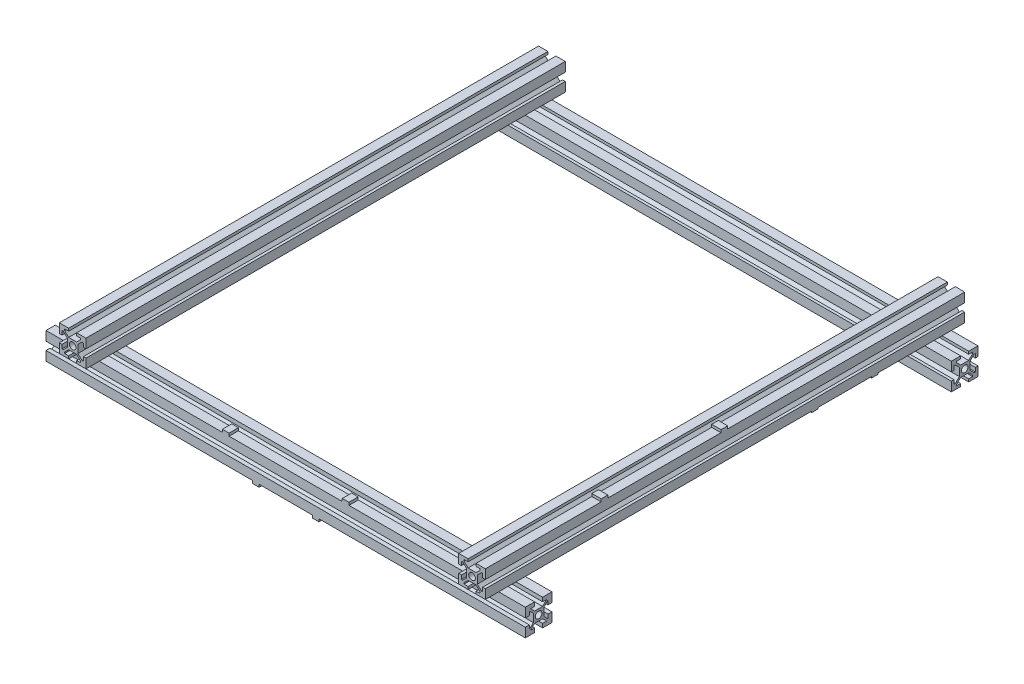
SolidWorks part; units mm, degrees
ref_plane "Front Plane" through (0, 0, 0) normal (0, 0, 1) x (1, 0, 0)
ref_plane "Top Plane" through (0, 0, 0) normal (0, 1, 0) x (1, 0, 0)
ref_plane "Right Plane" through (0, 0, 0) normal (1, 0, 0) x (0, 0, -1)
sketch "Sketch1" plane through (0, 0, 0) normal (0, 1, 0) x (1, 0, 0)
  line L1 (-180, 180) -> (180, 180)
  line L2 (-180, 180) -> (-180, -180)
  line L3 (-180, -180) -> (180, -180)
  line L4 (180, 180) -> (180, -180)
  line L5 (-180, 180) -> (180, -180) construction
  line L6 (-180, -180) -> (180, 180) construction
  point P0 (0, 0)
  dimension "D1" = 360
  dimension "D2" = 360
extrude "Boss-Extrude1" add sketch "Sketch1" along normal blind 20
sketch "Sketch2" plane through (0, 20, 0) normal (0, 1, 0) x (1, 0, 0)
  line L0 (-180, 180) -> (-180, -180) construction
  line L1 (-160, 160) -> (160, 160)
  line L2 (-160, 160) -> (-160, -160)
  line L3 (-160, -160) -> (160, -160)
  line L4 (160, 160) -> (160, -160)
  line L5 (-160, 160) -> (160, -160) construction
  line L6 (-160, -160) -> (160, 160) construction
  line L7 (-160, 160) -> (-140, 160)
  line L8 (-160, 160) -> (-160, -160)
  line L9 (-160, -160) -> (-140, -160)
  line L10 (-140, 160) -> (-140, -160)
  line L11 (160, 160) -> (140, 160)
  line L12 (160, 160) -> (160, -160)
  line L13 (160, -160) -> (140, -160)
  line L14 (140, 160) -> (140, -160)
  line L15 (-160, 160) -> (-180, 160)
  line L16 (-160, 160) -> (-160, -160)
  line L17 (-160, -160) -> (-180, -160)
  line L18 (-180, 160) -> (-180, -160)
  line L19 (180, -180) -> (180, 180) construction
  line L20 (160, 160) -> (180, 160)
  line L21 (160, 160) -> (160, -160)
  line L22 (160, -160) -> (180, -160)
  line L23 (180, 160) -> (180, -160)
  line L24 (180, 180) -> (-180, 180) construction
  line L25 (-140, 160) -> (140, 160)
  line L26 (-140, 160) -> (-140, 180)
  line L27 (-140, 180) -> (140, 180)
  line L28 (140, 160) -> (140, 180)
  line L29 (-180, -180) -> (180, -180) construction
  line L31 (-140, -180) -> (140, -180)
  line L32 (-140, -180) -> (-140, -160)
  line L33 (-140, -160) -> (140, -160)
  line L34 (140, -180) -> (140, -160)
  line L35 (160, -160) -> (180, -160)
  line L36 (160, -160) -> (160, -180)
  line L37 (160, -180) -> (180, -180)
  line L38 (180, -160) -> (180, -180)
  line L39 (-160, -160) -> (-180, -160)
  line L40 (-160, -160) -> (-160, -180)
  line L41 (-160, -180) -> (-180, -180)
  line L42 (-180, -160) -> (-180, -180)
  line L43 (-160, 160) -> (-180, 160)
  line L44 (-160, 160) -> (-160, 180)
  line L45 (-160, 180) -> (-180, 180)
  line L46 (-180, 160) -> (-180, 180)
  line L47 (160, 160) -> (180, 160)
  line L48 (160, 160) -> (160, 180)
  line L49 (160, 180) -> (180, 180)
  line L50 (180, 160) -> (180, 180)
  point P0 (0, 0)
  line M17 (180, -180) -> (180, 180)
  line M19 (-180, 180) -> (-180, -180)
  dimension "D1" = 320
  dimension "D2" = 320
  dimension "D3" = 20
  dimension "D4" = 20
extrude "Cut-Extrude1" cut sketch "Sketch2" against normal through all contours L17 L2 L15 M19 | L4 L22 L20 M17 | L14 L1 L10 L3
sketch "Sketch3" plane through (0, 0, 0) normal (0, -1, 0) x (1, 0, 0)
  line L1 (-180, 180) -> (180, 180)
  line L2 (-180, 180) -> (-180, 160)
  line L3 (-180, 160) -> (180, 160)
  line L4 (180, 180) -> (180, 160)
  line L5 (-180, -160) -> (180, -160)
  line L6 (-180, -160) -> (-180, -180)
  line L7 (-180, -180) -> (180, -180)
  line L8 (180, -160) -> (180, -180)
extrude "Boss-Extrude2" add sketch "Sketch3" along normal blind 20
sketch "Sketch4" plane through (0, 20, 0) normal (0, 1, 0) x (1, 0, 0)
  line L0 (-180, -180) -> (180, -180) construction
  line L1 (160, -160) -> (180, -160)
  line L2 (160, -160) -> (160, -180)
  line L3 (160, -180) -> (180, -180)
  line L4 (180, -160) -> (180, -180)
  line L5 (-180, -160) -> (-160, -160)
  line L6 (-180, -160) -> (-180, -180)
  line L7 (-180, -180) -> (-160, -180)
  line L8 (-160, -160) -> (-160, -180)
  line L10 (-180, 180) -> (-160, 180)
  line L11 (-180, 180) -> (-180, 160)
  line L12 (-180, 160) -> (-160, 160)
  line L13 (-160, 180) -> (-160, 160)
  line L14 (160, 160) -> (180, 160)
  line L15 (160, 160) -> (160, 180)
  line L16 (160, 180) -> (180, 180)
  line L17 (180, 160) -> (180, 180)
extrude "Cut-Extrude2" cut sketch "Sketch4" against normal blind 20
sketch "Sketch5" plane through (0, 20, 0) normal (0, 1, 0) x (1, 0, 0)
  line L0 (160, 180) -> (-160, 180) construction
  line L1 (-140, 160) -> (140, 160)
  line L2 (-140, 160) -> (-140, 180)
  line L3 (-140, 180) -> (140, 180)
  line L4 (140, 160) -> (140, 180)
  line L5 (-160, -180) -> (160, -180) construction
  line L6 (-140, -180) -> (140, -180)
  line L7 (-140, -180) -> (-140, -160)
  line L8 (-140, -160) -> (140, -160)
  line L9 (140, -180) -> (140, -160)
extrude "Cut-Extrude3" cut sketch "Sketch5" against normal blind 20
sketch "Sketch6" plane through (0, 0, -160) normal (0, 0, 1) x (1, 0, 0)
  line L1 (-180, 0) -> (180, 0)
  line L2 (-180, 0) -> (-180, -20)
  line L3 (-180, -20) -> (180, -20)
  line L4 (180, 0) -> (180, -20)
extrude "Boss-Extrude3" add sketch "Sketch6" along normal blind 10
sketch "Sketch7" plane through (0, 0, 160) normal (0, 0, -1) x (-1, 0, 0)
  line L1 (-180, 0) -> (180, 0)
  line L2 (-180, 0) -> (-180, -20)
  line L3 (-180, -20) -> (180, -20)
  line L4 (180, 0) -> (180, -20)
extrude "Boss-Extrude4" add sketch "Sketch7" along normal blind 10
sketch "Sketch8" plane through (0, 0, -180) normal (0, 0, -1) x (-1, 0, 0)
  line L1 (-180, 0) -> (180, 0)
  line L2 (-180, 0) -> (-180, -20)
  line L3 (-180, -20) -> (180, -20)
  line L4 (180, 0) -> (180, -20)
extrude "Cut-Extrude4" cut sketch "Sketch8" against normal blind 10
sketch "Sketch9" plane through (0, 0, 180) normal (0, 0, 1) x (1, 0, 0)
  line L1 (180, 0) -> (-180, 0)
  line L2 (180, 0) -> (180, -20)
  line L3 (180, -20) -> (-180, -20)
  line L4 (-180, 0) -> (-180, -20)
extrude "Cut-Extrude5" cut sketch "Sketch9" against normal blind 10
sketch "Sketch10" plane through (0, 0, -180) normal (0, 0, -1) x (-1, 0, 0)
  line L0 (140, 20) -> (160, 0) construction
  circle A0 centre (150, 10) radius 2.5
  dimension "D1" = 5
extrude "Cut-Extrude6" cut sketch "Sketch10" against normal through all
sketch "Sketch11" plane through (0, 0, 180) normal (0, 0, 1) x (1, 0, 0)
  line L0 (-160, 20) -> (-140, 0)
  line L1 (-160, 0) -> (-140, 20)
  line L2 (-154, 14) -> (-146, 14)
  line L3 (-154, 14) -> (-154, 6)
  line L4 (-154, 6) -> (-146, 6)
  line L5 (-146, 14) -> (-146, 6)
  line L6 (-154, 14) -> (-146, 6) construction
  line L7 (-154, 6) -> (-146, 14) construction
  line L8 (-154, 14) -> (-153, 14)
  line L9 (-154, 14) -> (-154, 13)
  line L10 (-154, 13) -> (-153, 13)
  line L11 (-153, 14) -> (-153, 13)
  line L12 (-146, 14) -> (-147, 14)
  line L13 (-146, 14) -> (-146, 13)
  line L14 (-146, 13) -> (-147, 13)
  line L15 (-147, 14) -> (-147, 13)
  line L16 (-154, 6) -> (-153, 6)
  line L17 (-154, 6) -> (-154, 7)
  line L18 (-154, 7) -> (-153, 7)
  line L19 (-153, 6) -> (-153, 7)
  line L20 (-146, 6) -> (-147, 6)
  line L21 (-146, 6) -> (-146, 7)
  line L22 (-146, 7) -> (-147, 7)
  line L23 (-147, 6) -> (-147, 7)
  line L24 (-160, 20) -> (-156, 20)
  line L25 (-160, 20) -> (-160, 16)
  line L26 (-160, 16) -> (-156, 16)
  line L27 (-156, 20) -> (-156, 16)
  line L28 (-153, 14) -> (-156, 17)
  line L29 (-140, 20) -> (-144, 20)
  line L30 (-140, 20) -> (-140, 16)
  line L31 (-140, 16) -> (-144, 16)
  line L32 (-144, 20) -> (-144, 16)
  line L33 (-160, 0) -> (-156, 0)
  line L34 (-160, 0) -> (-160, 4)
  line L35 (-160, 4) -> (-156, 4)
  line L36 (-156, 0) -> (-156, 4)
  line L37 (-140, 0) -> (-144, 0)
  line L38 (-140, 0) -> (-140, 4)
  line L39 (-140, 4) -> (-144, 4)
  line L40 (-144, 0) -> (-144, 4)
  line L41 (-154, 13) -> (-157, 16)
  line L42 (-157, 16) -> (-157, 4) construction
  line L43 (-156, 17) -> (-144.0513, 17) construction
  line L44 (-144.0513, 17) -> (-144, 17) construction
  line L45 (-157, 4) -> (-154.0345, 7.0171)
  line L46 (-154.0345, 7.0171) -> (-153, 6)
  line L47 (-153, 6) -> (-156, 2.9486)
  line L48 (-156, 2.9486) -> (-144, 2.9486) construction
  line L49 (-144, 2.9486) -> (-142.9741, 3.9745) construction
  line L50 (-142.9741, 3.9745) -> (-142.9741, 16) construction
  line L51 (-142.9741, 16) -> (-146, 12.9741)
  line L52 (-147, 6) -> (-144, 2.9486)
  line L53 (-146, 7) -> (-142.9741, 3.9745)
  line L54 (-153, 14) -> (-147, 14)
  line L55 (-156, 20) -> (-144, 20)
  line L56 (-156, 20) -> (-156, 18)
  line L57 (-156, 18) -> (-144, 18)
  line L58 (-144, 20) -> (-144, 18)
  line L59 (-160, 16) -> (-158, 16)
  line L60 (-160, 16) -> (-160, 4)
  line L61 (-160, 4) -> (-158, 4)
  line L62 (-158, 16) -> (-158, 4)
  line L63 (-140, 16) -> (-142, 16)
  line L64 (-140, 16) -> (-140, 4)
  line L65 (-140, 4) -> (-142, 4)
  line L66 (-142, 16) -> (-142, 4)
  line L67 (-156, 0) -> (-144, 0)
  line L68 (-156, 0) -> (-156, 2)
  line L69 (-156, 2) -> (-144, 2)
  line L70 (-144, 0) -> (-144, 2)
  line L71 (-156, 17) -> (-156, 18.0394)
  line L72 (-156, 18.0394) -> (-144, 18)
  line L73 (-147, 14) -> (-144, 17)
  point P4 (-150, 10)
  dimension "D1" = 8
  dimension "D2" = 1
  dimension "D3" = 1
  dimension "D4" = 1
  dimension "D5" = 1
  dimension "D6" = 4
  dimension "D7" = 4
  dimension "D8" = 4
  dimension "D9" = 4
  dimension "D10" = 2
  dimension "D11" = 2
  dimension "D12" = 2
  dimension "D13" = 2
extrude "Cut-Extrude7" cut sketch "Sketch11" against normal through all contours L26 L62 L35 L45 L46 L3 L41 | L2 L73 L32 L57 L27 L28 | L66 L31 L51 L5 L53 L39 | L36 L69 L40 L52 L4 L47
sketch "Sketch12" plane through (0, 0, 180) normal (0, 0, 1) x (1, 0, 0)
  line L0 (-160, 20) -> (-140, 0) construction
  line L1 (-140, 0) -> (-160, 0) construction
  line L2 (-160.3254, 13) -> (-139.6746, 13)
  line L3 (-160.3254, 13) -> (-160.3254, 7)
  line L4 (-160.3254, 7) -> (-139.6746, 7)
  line L5 (-139.6746, 13) -> (-139.6746, 7)
  line L6 (-160.3254, 13) -> (-139.6746, 7) construction
  line L7 (-160.3254, 7) -> (-139.6746, 13) construction
  line L8 (-153, 20) -> (-147, 20)
  line L9 (-153, 20) -> (-153, 0)
  line L10 (-153, 0) -> (-147, 0)
  line L11 (-147, 20) -> (-147, 0)
  line L12 (-153, 20) -> (-147, 0) construction
  line L13 (-153, 0) -> (-147, 20) construction
  line L14 (-156, 18) -> (-144, 18) construction
  line L15 (-153, 20) -> (-147, 20)
  line L16 (-153, 20) -> (-153, 18)
  line L17 (-153, 18) -> (-147, 18)
  line L18 (-147, 20) -> (-147, 18)
  line L19 (-158, 16) -> (-158, 4) construction
  line L20 (-158, 13) -> (-160.0036, 13)
  line L21 (-158, 13) -> (-158, 7)
  line L22 (-158, 7) -> (-160.0036, 7)
  line L23 (-160.0036, 13) -> (-160.0036, 7)
  line L24 (-156, 2) -> (-144, 2) construction
  line L25 (-153, 0) -> (-147, 0)
  line L26 (-153, 0) -> (-153, 2)
  line L27 (-153, 2) -> (-147, 2)
  line L28 (-147, 0) -> (-147, 2)
  line L30 (-142.0115, 13) -> (-139.6746, 13)
  line L31 (-142.0115, 13) -> (-142.0115, 7)
  line L32 (-142.0115, 7) -> (-139.6746, 7)
  line L33 (-139.6746, 13) -> (-139.6746, 7)
  line L34 (-158, 7) -> (-160.3254, 7)
  line L35 (-158, 7) -> (-158, 13)
  line L36 (-158, 13) -> (-160.3254, 13)
  line L37 (-160.3254, 7) -> (-160.3254, 13)
  point P4 (-150, 10)
  point P9 (-150, 10)
  line M7 (-144, 2) -> (-156, 2)
  line M8 (-160, 20) -> (-160, 0)
  line M9 (-160, 0) -> (-140, 0)
  line M10 (-140, 0) -> (-140, 20)
  line M11 (-140, 20) -> (-160, 20)
  line M19 (-158, 4) -> (-158, 16)
  line M24 (-156, 18) -> (-144, 18)
  line M26 (-142, 16) -> (-142, 4)
  dimension "D1" = 6
  dimension "D2" = 6
extrude "Cut-Extrude9" cut sketch "Sketch12" against normal through all contours L23 L2 L3 L4 | L4 L2 M8 M19 | L4 L2 M26 M10 | L11 L9 M7 M9 | L11 L9 M11 M24
sketch "Sketch13" plane through (0, 0, 180) normal (0, 0, 1) x (1, 0, 0)
  line L0 (140, 20) -> (160, 0) construction
  line L1 (140, 0) -> (160, 20) construction
  line L2 (147, 14) -> (147, 6)
  line L3 (146, 14) -> (154, 14)
  line L4 (146, 14) -> (146, 6)
  line L5 (146, 6) -> (154, 6)
  line L6 (154, 14) -> (154, 6)
  line L7 (146, 14) -> (154, 6) construction
  line L8 (146, 6) -> (154, 14) construction
  line L9 (140, 20) -> (144, 20)
  line L10 (140, 20) -> (140, 16)
  line L11 (140, 16) -> (144, 16)
  line L12 (144, 20) -> (144, 16)
  line L13 (160, 20) -> (156, 20)
  line L14 (160, 20) -> (160, 16)
  line L15 (160, 16) -> (156, 16)
  line L16 (156, 20) -> (156, 16)
  line L17 (140, 0) -> (144, 0)
  line L18 (140, 0) -> (140, 4)
  line L19 (140, 4) -> (144, 4)
  line L20 (144, 0) -> (144, 4)
  line L21 (160, 0) -> (156, 0)
  line L22 (160, 0) -> (160, 4)
  line L23 (160, 4) -> (156, 4)
  line L24 (156, 0) -> (156, 4)
  line L25 (153, 14) -> (153, 6)
  line L26 (144, 17) -> (157, 17)
  line L27 (146, 13) -> (154, 13)
  line L28 (146, 7) -> (154, 7)
  line L29 (144, 16) -> (143, 16)
  line L30 (144, 16) -> (144, 17)
  line L31 (144, 17) -> (143, 17)
  line L32 (143, 16) -> (143, 17)
  line L33 (157, 17) -> (157, 3)
  line L34 (157, 3) -> (143, 3)
  line L35 (143, 3) -> (143, 16)
  line L36 (143, 16) -> (146, 13)
  line L37 (144, 17) -> (147, 14)
  line L38 (153, 14) -> (156, 17)
  line L39 (154, 13) -> (157, 16)
  line L40 (157, 16) -> (156, 17)
  line L41 (146, 7) -> (143, 4)
  line L42 (143, 4) -> (144, 3)
  line L43 (144, 3) -> (147, 6)
  line L44 (153, 6) -> (156, 3)
  line L45 (156, 3) -> (157, 4)
  line L46 (157, 4) -> (154, 7)
  line L47 (150, 0) -> (150, 2) construction
  line L48 (140, 16) -> (142, 16)
  line L49 (140, 16) -> (140, 4)
  line L50 (140, 4) -> (142, 4)
  line L51 (142, 16) -> (142, 4)
  line L52 (144, 20) -> (156, 20)
  line L53 (144, 20) -> (144, 18)
  line L54 (144, 18) -> (156, 18)
  line L55 (156, 20) -> (156, 18)
  line L56 (160, 16) -> (158, 16)
  line L57 (160, 16) -> (160, 4)
  line L58 (160, 4) -> (158, 4)
  line L59 (158, 16) -> (158, 4)
  line L60 (144, 0) -> (156, 0)
  line L61 (144, 0) -> (144, 2)
  line L62 (144, 2) -> (156, 2)
  line L63 (156, 0) -> (156, 2)
  line L64 (158, 10) -> (160, 10) construction
  line L65 (150, 18) -> (150, 20) construction
  line L66 (142, 10) -> (140, 10) construction
  line L68 (140, 13) -> (142, 13)
  line L69 (140, 13) -> (140, 7)
  line L70 (140, 7) -> (142, 7)
  line L71 (142, 13) -> (142, 7)
  line L72 (140, 13) -> (142, 7) construction
  line L73 (140, 7) -> (142, 13) construction
  line L74 (158, 13) -> (160, 13)
  line L75 (158, 13) -> (158, 7)
  line L76 (158, 7) -> (160, 7)
  line L77 (160, 13) -> (160, 7)
  line L78 (158, 13) -> (160, 7) construction
  line L79 (158, 7) -> (160, 13) construction
  line L80 (147, 20) -> (153, 20)
  line L81 (147, 20) -> (147, 18)
  line L82 (147, 18) -> (153, 18)
  line L83 (153, 20) -> (153, 18)
  line L84 (147, 20) -> (153, 18) construction
  line L85 (147, 18) -> (153, 20) construction
  line L86 (147, 2) -> (153, 2)
  line L87 (147, 2) -> (147, 0)
  line L88 (147, 0) -> (153, 0)
  line L89 (153, 2) -> (153, 0)
  line L90 (147, 2) -> (153, 0) construction
  line L91 (147, 0) -> (153, 2) construction
  circle A0 centre (150, 10) radius 2.5
  point P62 (141, 10)
  point P67 (159, 10)
  point P72 (150, 19)
  point P77 (150, 1)
  dimension "D1" = 5
  dimension "D2" = 8
  dimension "D3" = 4
  dimension "D4" = 1
  dimension "D5" = 1
  dimension "D6" = 1
  dimension "D7" = 1
  dimension "D8" = 1
  dimension "D9" = 2
  dimension "D10" = 2
  dimension "D11" = 2
extrude "Cut-Extrude11" cut sketch "Sketch13" against normal through all contours L3 L38 L26 L37 | L54 L12 L26 L16 | L83 L52 L81 L54 | L41 L4 L36 L35 | L11 L51 L19 L35 | L44 L5 L43 L34 | L20 L62 L24 L34 | L49 L70 L51 L68 | L89 L62 L87 L60 | L59 L76 L57 L74 | L59 L15 L33 L23 | L46 L33 L39 L6 | A0
sketch "Sketch15" plane through (-180, 0, 0) normal (-1, 0, 0) x (0, 0, 1)
  line L0 (170, 0) -> (150, -20) construction
  line L1 (170, -20) -> (150, 0) construction
  line L2 (164, -7) -> (156, -7)
  line L3 (164, -6) -> (156, -6)
  line L4 (164, -6) -> (164, -14)
  line L5 (164, -14) -> (156, -14)
  line L6 (156, -6) -> (156, -14)
  line L7 (164, -6) -> (156, -14) construction
  line L8 (164, -14) -> (156, -6) construction
  line L9 (170, 0) -> (166, 0)
  line L10 (170, 0) -> (170, -4)
  line L11 (170, -4) -> (166, -4)
  line L12 (166, 0) -> (166, -4)
  line L13 (150, 0) -> (154, 0)
  line L14 (150, 0) -> (150, -4)
  line L15 (150, -4) -> (154, -4)
  line L16 (154, 0) -> (154, -4)
  line L17 (170, -20) -> (166, -20)
  line L18 (170, -20) -> (170, -16)
  line L19 (170, -16) -> (166, -16)
  line L20 (166, -20) -> (166, -16)
  line L21 (150, -20) -> (154, -20)
  line L22 (150, -20) -> (150, -16)
  line L23 (150, -16) -> (154, -16)
  line L24 (154, -20) -> (154, -16)
  line L25 (164, -13) -> (156, -13)
  line L26 (163, -6) -> (163, -14)
  line L27 (157, -6) -> (157, -14)
  line L28 (170, -3) -> (150, -3)
  line L29 (170, -17) -> (150, -17)
  line L30 (167, 0) -> (167, -20.1581)
  line L31 (153, 0) -> (153, -20)
  line L32 (157, -6) -> (154, -3)
  line L33 (156, -7) -> (153, -4)
  line L34 (163, -6) -> (166, -3)
  line L35 (164, -7) -> (167, -4)
  line L36 (164, -13) -> (167, -16)
  line L37 (163, -14) -> (166, -17)
  line L38 (157, -14) -> (154, -17)
  line L39 (156, -13) -> (153, -16)
  line L40 (166, 0) -> (154, -3) construction
  line L41 (150, -16) -> (153, -4) construction
  line L42 (154, -17) -> (166, -20) construction
  line L43 (170, -4) -> (167, -16) construction
  line L44 (150, 0) -> (150, -20) construction
  line L45 (163, 0) -> (157, 0)
  line L46 (163, 0) -> (163, -3)
  line L47 (163, -3) -> (157, -3)
  line L48 (157, 0) -> (157, -3)
  line L49 (163, 0) -> (157, -3) construction
  line L50 (163, -3) -> (157, 0) construction
  line L51 (153, -7) -> (150, -7)
  line L52 (153, -7) -> (153, -13)
  line L53 (153, -13) -> (150, -13)
  line L54 (150, -7) -> (150, -13)
  line L55 (153, -7) -> (150, -13) construction
  line L56 (153, -13) -> (150, -7) construction
  line L57 (150, -20) -> (170, -20) construction
  line L58 (163, -17) -> (157, -17)
  line L59 (163, -17) -> (163, -20)
  line L60 (163, -20) -> (157, -20)
  line L61 (157, -17) -> (157, -20)
  line L62 (163, -17) -> (157, -20) construction
  line L63 (163, -20) -> (157, -17) construction
  line L65 (170, -7) -> (167, -7)
  line L66 (170, -7) -> (170, -13)
  line L67 (170, -13) -> (167, -13)
  line L68 (167, -7) -> (167, -13)
  line L69 (170, -7) -> (167, -13) construction
  line L70 (170, -13) -> (167, -7) construction
  circle A0 centre (160, -10) radius 2.5
  point P49 (160, -1.5)
  point P55 (151.5, -10)
  point P62 (160, -18.5)
  point P69 (168.5, -10)
  dimension "D1" = 5
  dimension "D2" = 8
  dimension "D3" = 4
  dimension "D4" = 4
  dimension "D5" = 4
  dimension "D6" = 4
  dimension "D7" = 1
  dimension "D8" = 1
  dimension "D9" = 1
  dimension "D10" = 1
  dimension "D11" = 1
  dimension "D12" = 1
  dimension "D13" = 1
  dimension "D14" = 1
extrude "Cut-Extrude12" cut sketch "Sketch15" against normal through all contours L5 L38 L29 L37 | L29 L61 L60 L59 | L67 L66 L65 L30 | L51 L54 L53 L31 | L39 L6 L33 L31 | L3 L34 L28 L32 | L45 L48 L28 L46 | L4 L36 L30 L35 | A0
sketch "Sketch16" plane through (180, 0, 0) normal (1, 0, 0) x (0, 0, -1)
  line L0 (150, 0) -> (170, -20) construction
  line L1 (150, -20) -> (170, 0) construction
  line L2 (156, -7) -> (164, -7) construction
  line L3 (156, -6) -> (164, -6)
  line L4 (156, -6) -> (156, -14)
  line L5 (156, -14) -> (164, -14)
  line L6 (164, -6) -> (164, -14)
  line L7 (156, -6) -> (164, -14) construction
  line L8 (156, -14) -> (164, -6) construction
  line L9 (150, 0) -> (154, 0)
  line L10 (150, 0) -> (150, -4)
  line L11 (150, -4) -> (154, -4)
  line L12 (154, 0) -> (154, -4)
  line L13 (170, 0) -> (166, 0)
  line L14 (170, 0) -> (170, -4)
  line L15 (170, -4) -> (166, -4)
  line L16 (166, 0) -> (166, -4)
  line L17 (150, -20) -> (154, -20)
  line L18 (150, -20) -> (150, -16)
  line L19 (150, -16) -> (154, -16)
  line L20 (154, -20) -> (154, -16)
  line L21 (170, -20) -> (166, -20)
  line L22 (170, -20) -> (170, -16)
  line L23 (170, -16) -> (166, -16)
  line L24 (166, -20) -> (166, -16)
  line L25 (156, -13) -> (164, -13) construction
  line L26 (157, -6) -> (157, -14) construction
  line L27 (163, -6) -> (163, -14) construction
  line L28 (154, -3) -> (166, -3) construction
  line L29 (154, -17) -> (166, -17) construction
  line L30 (167, -4) -> (167, -16) construction
  line L31 (153, -4) -> (153, -16) construction
  line L32 (156, -7) -> (153, -4)
  line L33 (154, -3) -> (157, -6)
  line L34 (166, -3) -> (163, -6)
  line L35 (167, -4) -> (164, -7)
  line L36 (167, -16) -> (164, -13)
  line L37 (166, -17) -> (163, -14)
  line L38 (154, -17) -> (157, -14)
  line L39 (153, -16) -> (156, -13)
  line L40 (170, -20) -> (150, -20) construction
  line L41 (157, 0) -> (163, 0)
  line L42 (157, 0) -> (157, -20)
  line L43 (157, -20) -> (163, -20)
  line L44 (163, 0) -> (163, -20)
  line L45 (157, 0) -> (163, -20) construction
  line L46 (157, -20) -> (163, 0) construction
  line L47 (170, 0) -> (170, -20) construction
  line L48 (150, -7) -> (170, -7)
  line L49 (150, -7) -> (150, -13)
  line L50 (150, -13) -> (170, -13)
  line L51 (170, -7) -> (170, -13)
  line L52 (150, -7) -> (170, -13) construction
  line L53 (150, -13) -> (170, -7) construction
  line L54 (152, -16) -> (152, -4)
  line L55 (157, 0) -> (163, 0)
  line L56 (157, 0) -> (157, -2)
  line L57 (157, -2) -> (163, -2)
  line L58 (163, 0) -> (163, -2)
  line L59 (150, -7) -> (152, -7)
  line L60 (150, -7) -> (150, -13)
  line L61 (150, -13) -> (152, -13)
  line L62 (152, -7) -> (152, -13)
  line L63 (157, -20) -> (163, -20)
  line L64 (157, -20) -> (157, -18)
  line L65 (157, -18) -> (163, -18)
  line L66 (163, -20) -> (163, -18)
  line L67 (170, -7) -> (168, -7)
  line L68 (170, -7) -> (170, -13)
  line L69 (170, -13) -> (168, -13)
  line L70 (168, -7) -> (168, -13)
  line L71 (154, -18) -> (166, -18)
  line L72 (168, -16) -> (168, -4)
  line L73 (154, -2) -> (166, -2)
  circle A0 centre (160, -10) radius 2.5
  line M17 (170, -20) -> (170, 0)
  line M18 (170, 0) -> (150, 0)
  line M19 (150, 0) -> (150, -20)
  line M20 (150, -20) -> (170, -20)
  dimension "D1" = 5
  dimension "D2" = 8
  dimension "D3" = 4
  dimension "D4" = 1
  dimension "D5" = 1
  dimension "D6" = 1
  dimension "D7" = 1
  dimension "D8" = 1
  dimension "D9" = 1
  dimension "D10" = 1
  dimension "D11" = 1
  dimension "D12" = 2
  dimension "D13" = 2
  dimension "D14" = 2
  dimension "D15" = 2
extrude "Cut-Extrude13" cut sketch "Sketch16" against normal through all contours L73 L44 L34 L16 | L57 L42 L3 L44 | L73 L12 L33 L42 | L42 L57 L44 M18 | L70 L48 L6 L50 | L48 L72 L15 L35 | L48 L70 L50 M17 | L23 L72 L50 L36 | L44 L71 L24 L37 | L42 L65 L44 L5 | L20 L71 L42 L38 | L65 L42 L44 M20 | L54 L19 L39 L50 | L54 L50 L4 L48 | L54 L48 L32 L11 | L50 L54 L48 M19 | A0
sketch "Sketch17" plane through (0, 0, 0) normal (0, -1, 0) x (1, 0, 0)
  line L0 (153, -150) -> (153, 150) construction
  line L1 (160, -150) -> (153, -150)
  line L2 (160, -150) -> (160, -110)
  line L3 (160, -110) -> (153, -110)
  line L4 (153, -150) -> (153, -110)
  line L6 (160, -110) -> (153, -110)
  line L7 (160, -110) -> (160, -70)
  line L8 (160, -70) -> (153, -70)
  line L9 (153, -110) -> (153, -70)
  line L10 (160, -150) -> (160, 150) construction
  line L11 (153, -70) -> (160, -70)
  line L12 (153, -70) -> (153, -65)
  line L13 (153, -65) -> (160, -65)
  line L14 (160, -70) -> (160, -65)
  line L15 (153, -110) -> (160, -110)
  line L16 (153, -110) -> (153, -115)
  line L17 (153, -115) -> (160, -115)
  line L18 (160, -110) -> (160, -115)
  dimension "D1" = 40
  dimension "D2" = 40
  dimension "D3" = 5
  dimension "D4" = 5
extrude "Boss-Extrude6" add sketch "Sketch17" along normal blind 1 contours L0 L17 L2 L3 | L13 L0 L8 L11
sketch "Sketch18" plane through (0, 0, 0) normal (0, -1, 0) x (1, 0, 0)
  line L0 (-153, -150) -> (-153, 150) construction
  line L1 (-160, -150) -> (-153, -150)
  line L2 (-160, -150) -> (-160, -110)
  line L3 (-160, -110) -> (-153, -110)
  line L4 (-153, -150) -> (-153, -110)
  line L5 (-153, -180) -> (-153, 180) construction
  line L6 (-160, -110) -> (-153, -110)
  line L7 (-160, -110) -> (-160, -70)
  line L8 (-160, -70) -> (-153, -70)
  line L9 (-153, -110) -> (-153, -70)
  line L10 (-160, -150) -> (-160, 150) construction
  line L11 (-153, -70) -> (-160, -70)
  line L12 (-153, -70) -> (-153, -65)
  line L13 (-153, -65) -> (-160, -65)
  line L14 (-160, -70) -> (-160, -65)
  line L16 (-160, -110) -> (-153, -110)
  line L17 (-160, -110) -> (-160, -115)
  line L18 (-160, -115) -> (-153, -115)
  line L19 (-153, -110) -> (-153, -115)
  line M5 (-153, -150) -> (-153, 150)
  line M7 (-160, 150) -> (-160, -150)
  dimension "D1" = 5
  dimension "D2" = 40
  dimension "D3" = 40
  dimension "D4" = 5
extrude "Boss-Extrude7" add sketch "Sketch18" along normal blind 1 contours L13 L8 M5 M7 | L18 L4 L3 M7
sketch "Sketch19" plane through (0, 0, 0) normal (0, 1, 0) x (1, 0, 0)
  line L0 (-140, -163) -> (140, -170) construction
  line L1 (-140, -170) -> (140, -170) construction
  line L2 (-42.5, -163) -> (42.5, -163)
  line L3 (-42.5, -163) -> (-42.5, -170)
  line L4 (-42.5, -170) -> (42.5, -170)
  line L5 (42.5, -163) -> (42.5, -170)
  line L6 (-42.5, -163) -> (42.5, -170) construction
  line L7 (-42.5, -170) -> (42.5, -163) construction
  line L9 (-42.5, -163) -> (-47.5, -163)
  line L10 (-42.5, -163) -> (-42.5, -170)
  line L11 (-42.5, -170) -> (-47.5, -170)
  line L12 (-47.5, -163) -> (-47.5, -170)
  line L13 (42.5, -163) -> (47.5, -163)
  line L14 (42.5, -163) -> (42.5, -170)
  line L15 (42.5, -170) -> (47.5, -170)
  line L16 (47.5, -163) -> (47.5, -170)
  point P4 (0, -166.5)
  line M4 (140, -163) -> (-140, -163)
  line M6 (-140, -170) -> (140, -170)
  dimension "D1" = 85
  dimension "D2" = 5
  dimension "D3" = 5
extrude "Boss-Extrude10" add sketch "Sketch19" along normal blind 2 contours L12 L3 M4 M6 | L16 L5 M4 M6
sketch "Sketch20" plane through (0, -20, 0) normal (0, -1, 0) x (1, 0, 0)
  line L0 (-180, 170) -> (180, 150) construction
  line L1 (180, 150) -> (-180, 150) construction
  line L2 (-20, 170) -> (20, 170)
  line L3 (-20, 170) -> (-20, 150)
  line L4 (-20, 150) -> (20, 150)
  line L5 (20, 170) -> (20, 150)
  line L6 (-20, 170) -> (20, 150) construction
  line L7 (-20, 150) -> (20, 170) construction
  line L8 (180, 163) -> (-180, 163) construction
  line L9 (-20, 170) -> (-25, 170)
  line L10 (-20, 170) -> (-20, 163)
  line L11 (-20, 163) -> (-25, 163)
  line L12 (-25, 170) -> (-25, 163)
  line L14 (20, 170) -> (25, 170)
  line L15 (20, 170) -> (20, 163)
  line L16 (20, 163) -> (25, 163)
  line L17 (25, 170) -> (25, 163)
  point P4 (0, 160)
  line M6 (-180, 163) -> (180, 163)
  line M8 (180, 170) -> (-180, 170)
  dimension "D1" = 40
  dimension "D2" = 5
  dimension "D3" = 5
extrude "Boss-Extrude11" add sketch "Sketch20" along normal blind 2 contours L12 L3 M8 M6 | L17 L5 M8 M6
sketch "Sketch21" plane through (0, 20, 0) normal (0, 1, 0) x (1, 0, 0)
  line L0 (160, 180) -> (160, -180) construction
  line L1 (160, -88.0267) -> (153, -88.0267)
  line L2 (160, -88.0267) -> (160, -3.0267)
  line L3 (160, -3.0267) -> (153, -3.0267)
  line L4 (153, -88.0267) -> (153, -3.0267)
  line L5 (153, 180) -> (153, -180) construction
  line L7 (153, -88.0267) -> (160, -88.0267)
  line L8 (153, -88.0267) -> (153, -93.0267)
  line L9 (153, -93.0267) -> (160, -93.0267)
  line L10 (160, -88.0267) -> (160, -93.0267)
  line L11 (153, -3.0267) -> (160, -3.0267)
  line L12 (153, -3.0267) -> (153, 1.9733)
  line L13 (153, 1.9733) -> (160, 1.9733)
  line L14 (160, -3.0267) -> (160, 1.9733)
  point P12 (0, 0)
  line M8 (153, 180) -> (153, -180)
  line M10 (160, -180) -> (160, 180)
  dimension "D1" = 85
  dimension "D2" = 5
  dimension "D3" = 5
extrude "Boss-Extrude12" add sketch "Sketch21" along normal blind 2 contours L13 L3 M8 M10 | L9 L1 M8 M10
